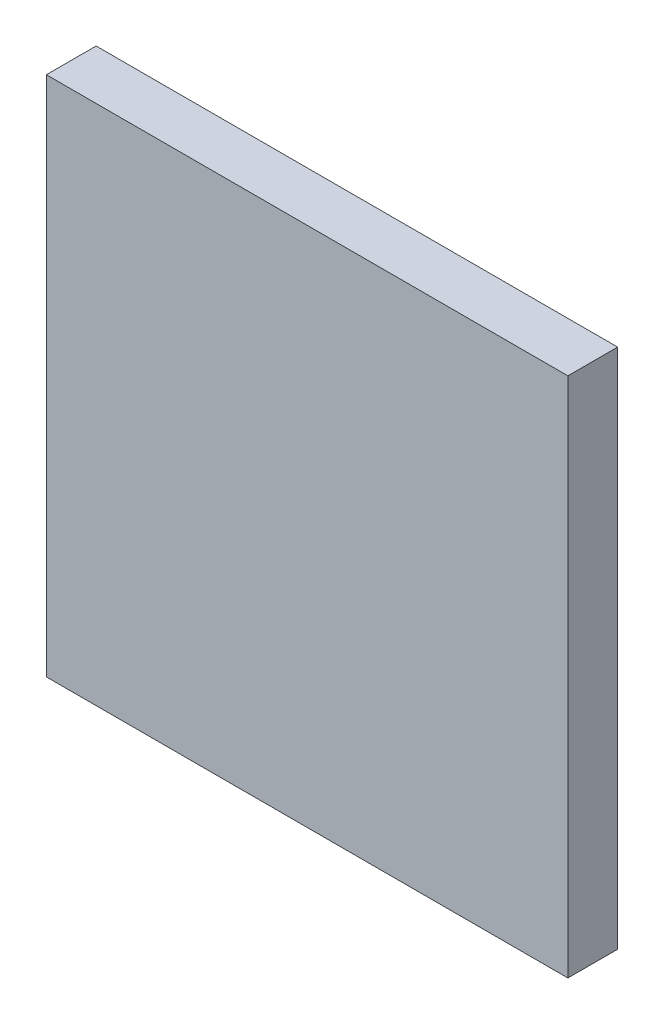
SolidWorks part; units mm, degrees
ref_plane "Front Plane" through (0, 0, 0) normal (0, 0, 1) x (1, 0, 0)
ref_plane "Top Plane" through (0, 0, 0) normal (0, 1, 0) x (1, 0, 0)
ref_plane "Right Plane" through (0, 0, 0) normal (1, 0, 0) x (0, 0, -1)
sketch "Sketch1" plane through (0, 0, 0) normal (0, 0, 1) x (1, 0, 0)
  line L4 (-42.84, -25) -> (-42.84, -60)
  line L5 (-42.84, -60) -> (-7.84, -60)
  line L6 (-7.84, -60) -> (-7.84, -25)
  line L7 (-7.84, -25) -> (-42.84, -25)
  line L8 (-42.84, -25) -> (-42.84, -60)
  line L9 (-42.84, -60) -> (-7.84, -60)
  line L10 (-7.84, -60) -> (-7.84, -25)
  line L11 (-7.84, -25) -> (-42.84, -25)
  dimension "D1" = 0
extrude "Extrude1" add sketch "Sketch1" along normal blind 3.34
